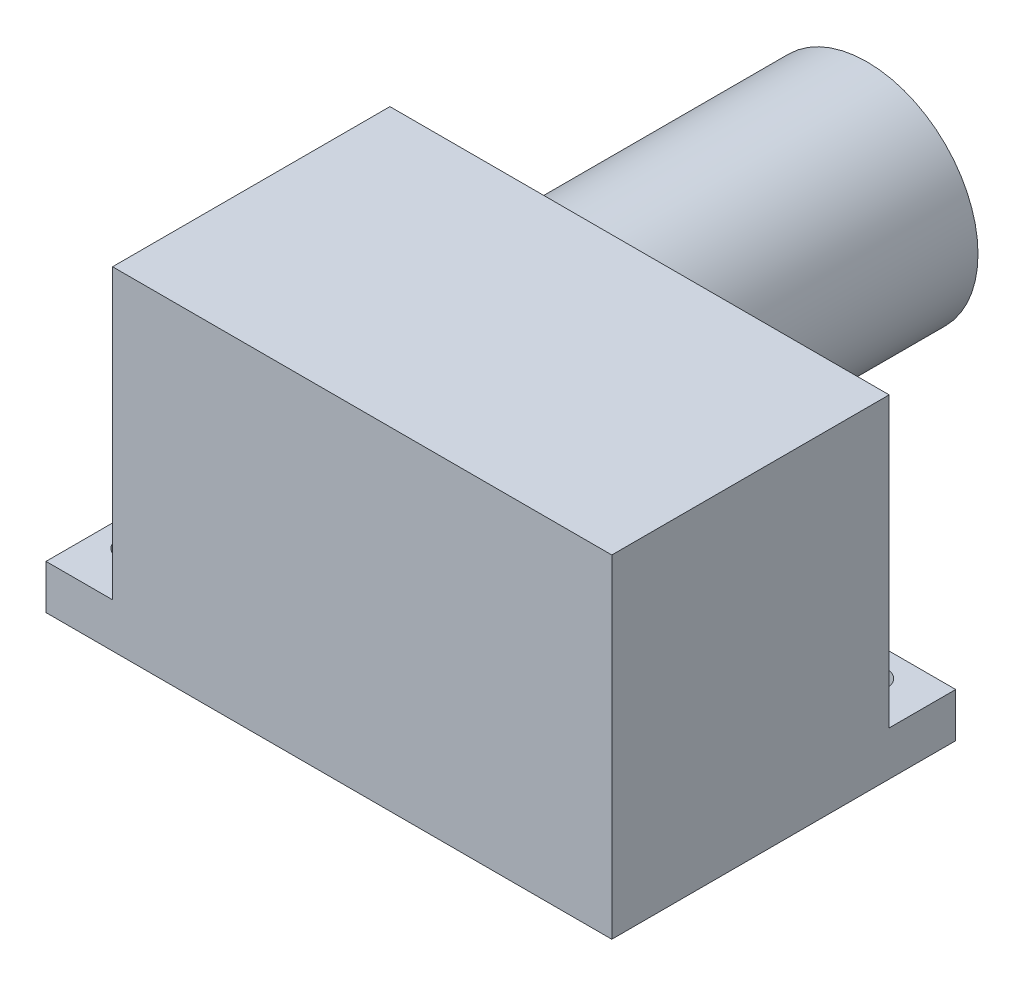
SolidWorks part; units mm, degrees
ref_plane "Plan de face" through (0, 0, 0) normal (0, 0, 1) x (1, 0, 0)
ref_plane "Plan de dessus" through (0, 0, 0) normal (0, 1, 0) x (1, 0, 0)
ref_plane "Plan de droite" through (0, 0, 0) normal (1, 0, 0) x (0, 0, -1)
sketch "Esquisse1" plane through (0, 0, 0) normal (0, 0, 1) x (1, 0, 0)
  line L1 (-22.5, -15) -> (22.5, -15)
  line L2 (-22.5, -15) -> (-22.5, 15)
  line L3 (-22.5, 15) -> (22.5, 15)
  line L4 (22.5, -15) -> (22.5, 15)
  line L5 (-22.5, -15) -> (22.5, 15) construction
  line L6 (-22.5, 15) -> (22.5, -15) construction
  point P0 (0, 0)
extrude "Boss.-Extru.1" add sketch "Esquisse1" along normal blind 25
sketch "Esquisse2" plane through (0, 0, 0) normal (0, 0, -1) x (-1, 0, 0)
  circle A0 centre (9.4921, 0) radius 10
extrude "Boss.-Extru.2" add sketch "Esquisse2" along normal blind 30
sketch "Esquisse3" plane through (-22.5, 0, 0) normal (-1, 0, 0) x (0, 0, 1)
  line L1 (25, -15) -> (15, -15)
  line L2 (25, -15) -> (25, -11)
  line L3 (25, -11) -> (15, -11)
  line L4 (15, -15) -> (15, -11)
  dimension "D1" = 4
  dimension "D2" = 10
extrude "Boss.-Extru.3" add sketch "Esquisse3" along normal blind 6 contours L3 L4 L1 L2
sketch "Esquisse4" plane through (0, -11, 0) normal (0, 1, 0) x (1, 0, 0)
  circle A0 centre (-25.5296, -20) radius 1.5
  dimension "D1" = 3
extrude "Enlèv. mat.-Extru.1" cut sketch "Esquisse4" against normal blind 6 contours A0
sketch "Esquisse6" plane through (0, 0, 0) normal (0, 0, -1) x (-1, 0, 0)
  line L1 (-22.5, -15) -> (-12.5, -15)
  line L2 (-22.5, -15) -> (-22.5, -11)
  line L3 (-22.5, -11) -> (-12.5, -11)
  line L4 (-12.5, -15) -> (-12.5, -11)
  dimension "D1" = 10
  dimension "D2" = 4
extrude "Boss.-Extru.4" add sketch "Esquisse6" along normal blind 6 contours L3 L4 L1 L2
sketch "Esquisse7" plane through (0, -11, 0) normal (0, 1, 0) x (1, 0, 0)
  line L0 (22.5, 0) -> (12.5, 0) construction
  circle A0 centre (17.7894, 3) radius 1.5
  dimension "D1" = 3
  dimension "D2" = 3
extrude "Enlèv. mat.-Extru.2" cut sketch "Esquisse7" against normal blind 6 contours A0
